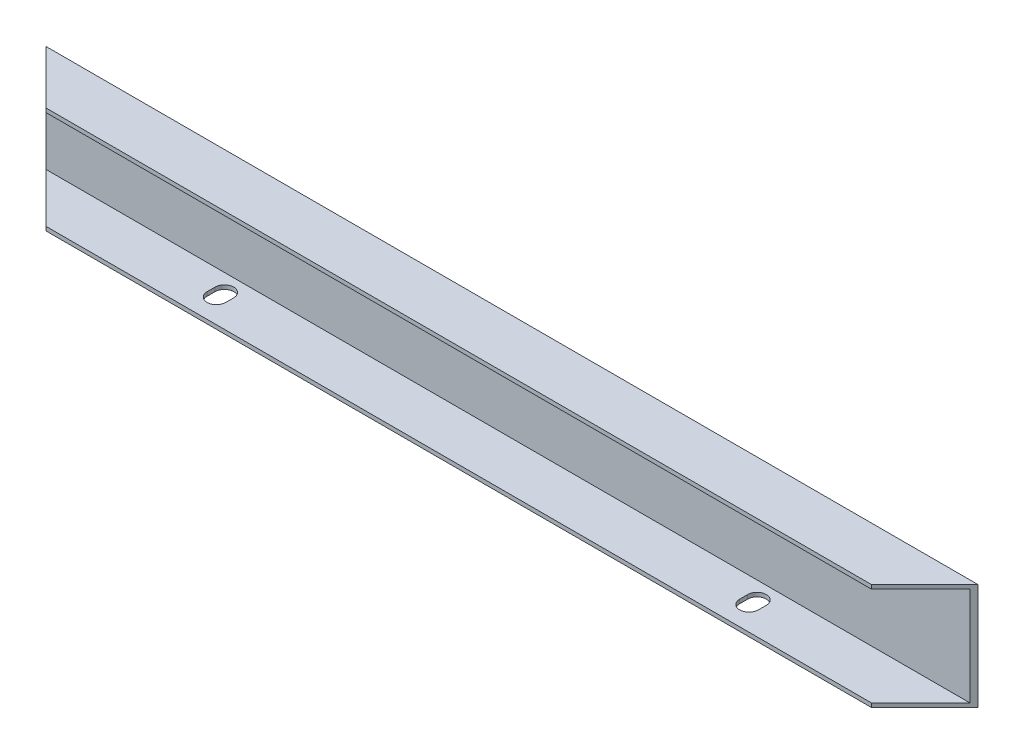
SolidWorks part; units mm, degrees
material "6061-O (SS)"
ref_plane "Plano frontal" through (0, 0, 0) normal (0, 0, 1) x (1, 0, 0)
ref_plane "Plano superior" through (0, 0, 0) normal (0, 1, 0) x (1, 0, 0)
ref_plane "Plano direito" through (0, 0, 0) normal (1, 0, 0) x (0, 0, -1)
sketch "Esboço1" plane through (0, 0, 0) normal (1, 0, 0) x (0, 0, -1)
  line L0 (0, 20) -> (0, -20)
  line L1 (0, 20) -> (-20, 20)
  line L2 (-20, 20) -> (-20, 18.5)
  line L3 (-20, 18.5) -> (-1.5, 18.5)
  line L4 (-1.5, 18.5) -> (-1.5, -18.5)
  line L5 (-21.1028, 0) -> (4.5614, 0) construction
  line L6 (-20, -18.5) -> (-1.5, -18.5)
  line L7 (-20, -20) -> (-20, -18.5)
  line L8 (0, -20) -> (-20, -20)
  line L9 (-1.5, 18.5) -> (0, 18.5) construction
  dimension "D1" = 20
  dimension "D2" = 40
  dimension "D3" = 1.5
extrude "Ressalto-extrusão1" add sketch "Esboço1" along normal mid plane 350
sketch "Esboço2" plane through (0, 20, 0) normal (0, 1, 0) x (1, 0, 0)
  line L0 (-175, 0) -> (-155, -20)
  line L1 (175, -20) -> (-175, -20) construction
  line L2 (-155, -20) -> (-175, -20)
  line L3 (-175, -20) -> (-175, 0)
  line L4 (175, 0) -> (155, -20)
  line L5 (155, -20) -> (175, -20)
  line L6 (175, -20) -> (175, 0)
extrude "Corte-extrusão1" cut sketch "Esboço2" against normal mid plane 100
sketch "Esboço3" plane through (0, -20, 0) normal (0, -1, 0) x (1, 0, 0)
  line L0 (-103.5, 11) -> (-103.5, 8)
  line L1 (-96.5, 8) -> (-96.5, 11)
  line L2 (175, 0) -> (-175, 0) construction
  line L4 (0, 39.9882) -> (0, -11.8128) construction
  line L5 (96.5, 8) -> (96.5, 11)
  line L6 (103.5, 11) -> (103.5, 8)
  arc A0 (-103.5, 8) -> (-96.5, 8) centre (-100, 8) ccw
  arc A1 (-96.5, 11) -> (-103.5, 11) centre (-100, 11) ccw
  arc A2 (96.5, 11) -> (103.5, 11) centre (100, 11) cw
  arc A3 (103.5, 8) -> (96.5, 8) centre (100, 8) cw
  dimension "D1" = 8
  dimension "D2" = 3
  dimension "D4" = 200
  dimension "D3" = 7
extrude "Corte-extrusão2" cut sketch "Esboço3" against normal up to surface (1.5 mm away) up to face at (0, -18.5, 10.75)
